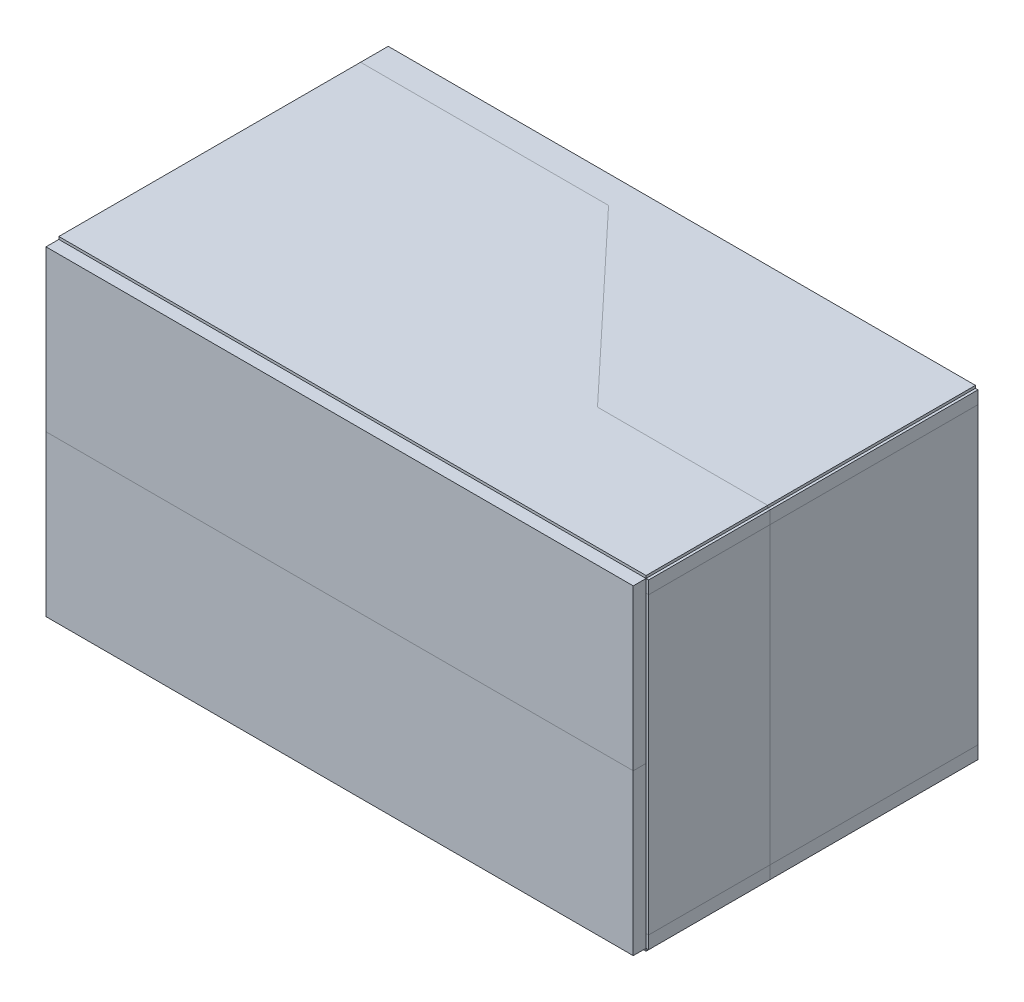
SolidWorks part; units mm, degrees
other "후면"
other "천장2"
other "천장1"
other "좌측면"
other "정면"
other "우측면"
other "바닥"
other "후면하단작음2"
other "후면상단작음2"
other "상단인테리어2"
other "하단인테리어2"
other "후면하단큼1"
other "후면상단큼1"
other "후면하단작음1"
other "후면상단작음1"
other "상단인테리어1"
other "하단인테리어1"
ref_plane "정면" through (0, 0, 0) normal (0, 0, 1) x (1, 0, 0)
ref_plane "윗면" through (0, 0, 0) normal (0, 1, 0) x (1, 0, 0)
ref_plane "우측면" through (0, 0, 0) normal (1, 0, 0) x (0, 0, -1)
sketch "스케치1" plane through (0, 0, 0) normal (0, 0, 1) x (1, 0, 0)
  line L1 (51, 74.896) -> (280, 74.896)
  line L2 (51, 74.896) -> (51, -50)
  line L3 (51, -50) -> (280, -50)
  line L4 (280, 74.896) -> (280, -50)
extrude "보스-돌출1" add sketch "스케치1" along normal up to surface (7.8606 mm away)
sketch "스케치2" plane through (0, 0, 7.8606) normal (0, 0, 1) x (1, 0, 0)
  line L0 (280, 74.896) -> (280, -50) construction
  line L1 (51, 74.896) -> (280, 74.896)
  line L2 (51, 74.896) -> (51, 69.896)
  line L3 (51, 69.896) -> (280, 69.896)
  line L4 (280, 74.896) -> (280, 69.896)
  dimension "D1" = 5
extrude "컷-돌출1" cut sketch "스케치2" against normal up to surface (7.8606 mm away) contours L1 L3 L2 up to face at (165.5, 12.448, 0)
sketch "스케치4" plane through (0, 0, 7.8606) normal (0, 0, 1) x (1, 0, 0)
  line L0 (280, 69.896) -> (280, -50) construction
  line L1 (51, -50) -> (280, -50)
  line L2 (51, -50) -> (51, -45)
  line L3 (51, -45) -> (280, -45)
  line L4 (280, -50) -> (280, -45)
  line M1 (280, -50) -> (280, 69.896)
  line M3 (51, 69.896) -> (51, -50)
  line M4 (51, -50) -> (280, -50)
  dimension "D1" = 5
extrude "컷-돌출2" cut sketch "스케치4" against normal up to surface (7.8606 mm away) contours L3 M3 M4 M1 up to face at (165.5, 9.948, 0)
sketch "스케치5" plane through (0, 0, 7.8606) normal (0, 0, 1) x (1, 0, 0)
  line L0 (51, -45) -> (280, -45) construction
  line L1 (280, 69.896) -> (275, 69.896)
  line L2 (280, 69.896) -> (280, -45)
  line L3 (280, -45) -> (275, -45)
  line L4 (275, 69.896) -> (275, -45)
  line M1 (51, -45) -> (280, -45)
  line M2 (280, -45) -> (280, 69.896)
  line M3 (280, 69.896) -> (51, 69.896)
  dimension "D1" = 5
extrude "컷-돌출3" cut sketch "스케치5" against normal up to surface (7.8606 mm away) contours L4 M3 M1 M2 up to face at (165.5, 12.448, 0)
sketch "스케치6" plane through (0, 69.896, 0) normal (0, 1, 0) x (1, 0, 0)
  line L1 (51, 0) -> (280, 0)
  line L2 (51, 0) -> (51, -128.4421)
  line L3 (51, -128.4421) -> (280, -128.4421)
  line L4 (280, 0) -> (280, -128.4421)
extrude "보스-돌출3" add sketch "스케치6" along normal blind 5 separate body
sketch "스케치7" plane through (0, 0, 7.8606) normal (0, 0, 1) x (1, 0, 0)
  line L0 (51, -45) -> (275, -45) construction
  line L1 (51, 69.896) -> (56, 69.896)
  line L2 (51, 69.896) -> (51, -45)
  line L3 (51, -45) -> (56, -45)
  line L4 (56, 69.896) -> (56, -45)
  dimension "D1" = 5
extrude "보스-돌출4" add sketch "스케치7" along normal up to surface (120.5815 mm away) separate body up to face at (165.5, 72.396, 128.4421)
sketch "스케치8" plane through (0, -45, 0) normal (0, -1, 0) x (1, 0, 0)
  line L1 (51, 128.4421) -> (280, 128.4421)
  line L2 (51, 128.4421) -> (51, 0)
  line L3 (51, 0) -> (280, 0)
  line L4 (280, 128.4421) -> (280, 0)
extrude "보스-돌출5" add sketch "스케치8" along normal blind 5 separate body
sketch "스케치9" plane through (0, 0, 128.4421) normal (0, 0, 1) x (1, 0, 0)
  line L1 (51, 74.896) -> (280, 74.896)
  line L2 (51, 74.896) -> (51, 12.446)
  line L3 (51, 12.446) -> (280, 12.446)
  line L4 (280, 74.896) -> (280, 12.446)
  dimension "D1" = 62.45
extrude "보스-돌출6" add sketch "스케치9" along normal blind 5 separate body
sketch "스케치10" plane through (0, 0, 128.4421) normal (0, 0, 1) x (1, 0, 0)
  line L1 (51, 12.446) -> (280, 12.446)
  line L2 (51, 12.446) -> (51, -50)
  line L3 (51, -50) -> (280, -50)
  line L4 (280, 12.446) -> (280, -50)
extrude "보스-돌출7" add sketch "스케치10" along normal blind 5 separate body
sketch "스케치11" plane through (275, 0, 0) normal (1, 0, 0) x (0, 0, -1)
  line L1 (0, -45) -> (-128.4421, -45)
  line L2 (0, -45) -> (0, 69.896)
  line L3 (0, 69.896) -> (-128.4421, 69.896)
  line L4 (-128.4421, -45) -> (-128.4421, 69.896)
extrude "보스-돌출8" add sketch "스케치11" along normal blind 5 separate body
sketch "스케치12" plane through (0, -50, 0) normal (0, -1, 0) x (1, 0, 0)
  line L0 (51, 10.7712) -> (147.7059, 10.7712)
  line L1 (51, 128.4421) -> (51, 0) construction
  line L2 (147.7059, 10.7712) -> (213.6585, 81.0356)
  line L3 (213.6585, 81.0356) -> (280, 81.0356)
  line L4 (280, 0) -> (280, 128.4421) construction
  line L5 (51, 10.7712) -> (51, 0)
  line L6 (51, 0) -> (280, 0)
  line L7 (280, 0) -> (280, 81.0356)
extrude "보스-돌출9" add sketch "스케치12" along normal blind 1 separate body
sketch "스케치13" plane through (0, -50, 0) normal (0, -1, 0) x (1, 0, 0)
  line L0 (51, 128.4421) -> (51, 10.7712)
  line L1 (51, 10.7712) -> (147.7059, 10.7712)
  line L2 (147.7059, 10.7712) -> (213.6585, 81.0356)
  line L3 (213.6585, 81.0356) -> (280, 81.0356)
  line L4 (280, 81.0356) -> (280, 128.4421)
  line L5 (280, 128.4421) -> (51, 128.4421)
extrude "보스-돌출10" add sketch "스케치13" along normal blind 1 separate body
sketch "스케치14" plane through (280, 0, 0) normal (1, 0, 0) x (0, 0, -1)
  line L1 (-81.0356, -50) -> (-128.4421, -50)
  line L2 (-81.0356, -50) -> (-81.0356, -45)
  line L3 (-81.0356, -45) -> (-128.4421, -45)
  line L4 (-128.4421, -50) -> (-128.4421, -45)
extrude "보스-돌출11" add sketch "스케치14" along normal blind 1 separate body
sketch "스케치15" plane through (280, 0, 0) normal (1, 0, 0) x (0, 0, -1)
  line L1 (-81.0356, -50) -> (0, -50)
  line L2 (-81.0356, -50) -> (-81.0356, -45)
  line L3 (-81.0356, -45) -> (0, -45)
  line L4 (0, -50) -> (0, -45)
extrude "보스-돌출12" add sketch "스케치15" along normal blind 1 separate body
sketch "스케치16" plane through (280, 0, 0) normal (1, 0, 0) x (0, 0, -1)
  line L0 (-128.4421, 69.896) -> (0, 69.896) construction
  line L1 (-128.4421, -45) -> (-81.0356, -45)
  line L2 (-128.4421, -45) -> (-128.4421, 69.896)
  line L3 (-128.4421, 69.896) -> (-81.0356, 69.896)
  line L4 (-81.0356, -45) -> (-81.0356, 69.896)
extrude "보스-돌출13" add sketch "스케치16" along normal blind 1 separate body
sketch "스케치17" plane through (280, 0, 0) normal (1, 0, 0) x (0, 0, -1)
  line L0 (0, 74.896) -> (0, 69.896) construction
  line L1 (-81.0356, -45) -> (0, -45)
  line L2 (-81.0356, -45) -> (-81.0356, 69.896)
  line L3 (-81.0356, 69.896) -> (0, 69.896)
  line L4 (0, -45) -> (0, 69.896)
  line L5 (-128.4421, 69.896) -> (0, 69.896) construction
extrude "보스-돌출14" add sketch "스케치17" along normal blind 1 separate body
ref_plane "평면1" through (0, 12.446, 0) normal (0, 1, 0) x (1, 0, 0)
mirror "대칭 복사2" about plane through (0, 12.446, 0) normal (0, 1, 0) of bodies 112 113 114 115
other "바디 저장1"
other "바디 저장2"
